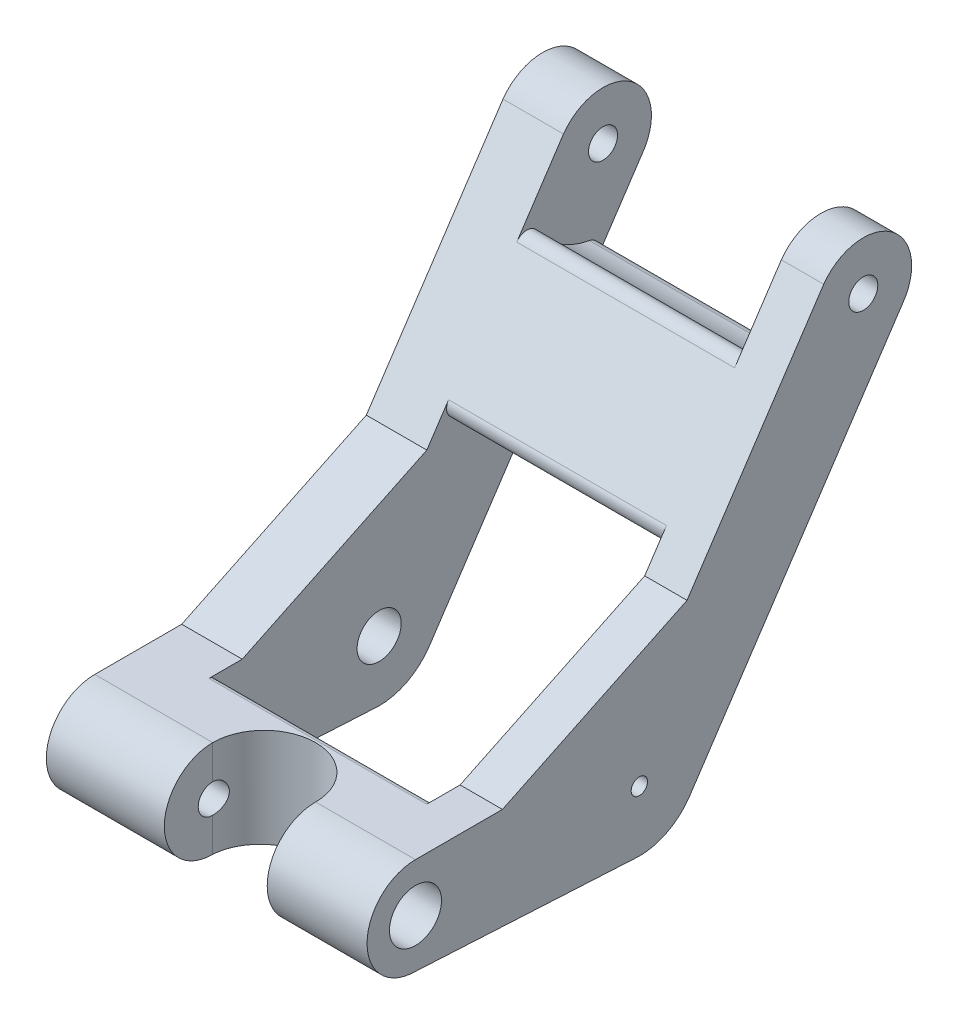
SolidWorks part; units mm, degrees
ref_plane "Front Plane" through (0, 0, 0) normal (0, 0, 1) x (1, 0, 0)
ref_plane "Top Plane" through (0, 0, 0) normal (0, 1, 0) x (1, 0, 0)
ref_plane "Right Plane" through (0, 0, 0) normal (1, 0, 0) x (0, 0, -1)
sketch "Sketch19" plane through (0, 0, 0) normal (1, 0, 0) x (0, 0, -1)
  line L0 (-37, 0) -> (0, 0) construction
  line L5 (0, 0) -> (37, 52) construction
  line L8 (-37, -8) -> (0, -10)
  line L9 (8.1479, -5.7976) -> (43.5183, 47.362)
  line L10 (30.4632, 56.6119) -> (7.8793, 22.6698)
  line L11 (7.8793, 22.6698) -> (-22.6274, 8)
  line L12 (-22.6274, 8) -> (-37, 8)
  arc A0 (8.1479, -5.7976) -> (0, -10) centre (0, 0) cw
  arc A1 (43.5183, 47.362) -> (30.4632, 56.6119) centre (37, 52) ccw
  arc A2 (-37, -8) -> (-37, 8) centre (-37, 0) cw
  circle A3 centre (37, 52) radius 2.4
  circle A4 centre (0, 0) radius 3.65
  circle A5 centre (-37, 0) radius 2.4
  circle A6 centre (0, 0) radius 24 construction
  point P0 (0, 0)
  point P1 (-37, 0)
  point P2 (37, 52)
  dimension "D3" = 37
  dimension "D11" = 7.3
  dimension "D12" = 4.8
  dimension "D13" = 4.8
  dimension "D5" = 8
  dimension "D6" = 10
  dimension "D7" = 8
  dimension "D1" = 37
  dimension "D2" = 52
  dimension "D4" = 0
extrude "Base" add sketch "Sketch19" along normal blind 10
sketch "Sketch20" plane through (10, 0, 0) normal (1, 0, 0) x (0, 0, -1)
  line L0 (30.4632, 56.6119) -> (7.8793, 22.6698) construction
  line L1 (8.1479, -5.7976) -> (43.5183, 47.362) construction
  line L2 (-22.6274, 8) -> (-37, 8) construction
  line L3 (-37, -8) -> (0, -10) construction
  line L7 (22.74, 45.0044) -> (11.4766, 28.0763)
  line L8 (24.3389, 18.5364) -> (36.0548, 36.1447)
  line L9 (-28.1425, 8) -> (-37, 8)
  line L10 (-37, -8) -> (-28.0716, -8.4826)
  circle A0 centre (0, 0) radius 24 construction
  arc A1 (12.2656, 25.1705) -> (21.1622, 18.3347) centre (0, 0) cw
  arc A2 (-27.1721, 6.7586) -> (-27.0515, -7.226) centre (0, 0) ccw
  arc A5 (26.087, 44.9787) -> (34.7383, 39.222) centre (37, 52) ccw
  arc A7 (-27.0515, -7.226) -> (-28.0716, -8.4826) centre (-28.0176, -7.4841) cw
  arc A9 (34.7383, 39.222) -> (36.0548, 36.1447) centre (34.3897, 37.2526) cw
  arc A10 (22.74, 45.0044) -> (26.087, 44.9787) centre (24.4051, 43.8965) cw
  arc A11 (12.2656, 25.1705) -> (11.4766, 28.0763) centre (13.1417, 26.9684) cw
  arc A12 (21.1622, 18.3347) -> (24.3389, 18.5364) centre (22.6738, 19.6443) ccw
  arc A13 (-37, 8) -> (-37, -8) centre (-37, 0) ccw
  arc A14 (-37, 8) -> (-37, -8) centre (-37, 0) ccw construction
  arc A15 (-28.1425, 8) -> (-27.1721, 6.7586) centre (-28.1425, 7) cw
  point P23 (-26.8328, 8)
  point P30 (-26.8328, 8)
  point P33 (-26.6598, -8.5589)
  point P39 (37.9956, 39.0616)
  point P42 (24.6809, 47.9216)
  point P45 (10.1569, 26.0929)
  point P48 (22.8101, 16.2388)
  dimension "D1" = 28
  dimension "D2" = 28
  dimension "D3" = 1
  dimension "D4" = 12.9766
  dimension "D8" = 1
  dimension "D10" = 2
  dimension "D11" = 2
  dimension "D12" = 2
  dimension "D13" = 2
extrude "Connector" add sketch "Sketch20" along normal blind 36
sketch "Sketch21" plane through (46, 0, 0) normal (1, 0, 0) x (0, 0, -1)
  line L1 (-22.6274, 8) -> (-28.1425, 8) construction
  line L2 (-28.1425, 8) -> (-37, 8) construction
  line L3 (-37, -8) -> (-28.0716, -8.4826) construction
  line L4 (-28.0716, -8.4826) -> (0, -10) construction
  line L5 (8.1479, -5.7976) -> (24.3389, 18.5364) construction
  line L6 (24.3389, 18.5364) -> (36.0548, 36.1447) construction
  line L7 (36.0548, 36.1447) -> (43.5183, 47.362) construction
  line L8 (30.4632, 56.6119) -> (22.74, 45.0044) construction
  line L9 (22.74, 45.0044) -> (11.4766, 28.0763) construction
  line L10 (11.4766, 28.0763) -> (7.8793, 22.6698) construction
  line L11 (7.8793, 22.6698) -> (-22.6274, 8) construction
  line L12 (-22.6274, 8) -> (-28.1425, 8)
  line L13 (-28.1425, 8) -> (-37, 8)
  line L14 (-37, -8) -> (-28.0716, -8.4826)
  line L15 (-28.0716, -8.4826) -> (0, -10)
  line L16 (8.1479, -5.7976) -> (24.3389, 18.5364)
  line L17 (24.3389, 18.5364) -> (36.0548, 36.1447)
  line L18 (36.0548, 36.1447) -> (43.5183, 47.362)
  line L19 (30.4632, 56.6119) -> (22.74, 45.0044)
  line L20 (22.74, 45.0044) -> (11.4766, 28.0763)
  line L21 (11.4766, 28.0763) -> (7.8793, 22.6698)
  line L22 (7.8793, 22.6698) -> (-22.6274, 8)
  arc A0 (-37, 8) -> (-37, -8) centre (-37, 0) ccw construction
  arc A1 (0, -10) -> (8.1479, -5.7976) centre (0, 0) ccw construction
  arc A2 (43.5183, 47.362) -> (30.4632, 56.6119) centre (37, 52) ccw construction
  arc A3 (-37, 8) -> (-37, -8) centre (-37, 0) ccw
  arc A4 (0, -10) -> (8.1479, -5.7976) centre (0, 0) ccw
  arc A5 (43.5183, 47.362) -> (30.4632, 56.6119) centre (37, 52) ccw
  circle A6 centre (37, 52) radius 2.4
  circle A7 centre (-37, 0) radius 2.4
  circle A8 centre (0, 0) radius 1.35
  dimension "D1" = 4.8
  dimension "D2" = 4.8
  dimension "D3" = 2.7
extrude "ThinPlate" add sketch "Sketch21" along normal blind 7
sketch "Sketch22" plane through (46, 0, 0) normal (-1, 0, 0) x (0, 0, 1)
  circle A0 centre (0, 0) radius 1.35
  circle A1 centre (0, 0) radius 3
  dimension "D1" = 6
  dimension "D2" = 2.7
extrude "Spacer" add sketch "Sketch22" along normal blind 6
sketch "Sketch23" plane through (0, 8, 0) normal (0, 1, 0) x (1, 0, 0)
  line L0 (10, -27.0176) -> (46, -27.0176) construction
  line L1 (46, -27.0176) -> (46, -45) construction
  line L2 (0, -45) -> (53, -45) construction
  line L3 (46, -45) -> (10, -45) construction
  line L4 (10, -45) -> (10, -27.0176) construction
  line L5 (28, -27.0176) -> (28, -45) construction
  line L6 (53, -37) -> (0, -37) construction
  line L7 (10, -37) -> (46, -37) construction
  line L8 (19.5, -37) -> (19.5, -45.5)
  line L9 (19.5, -28.5) -> (36.5, -28.5) construction
  line L10 (19.5, -28.5) -> (19.5, -45.5) construction
  line L11 (19.5, -45.5) -> (36.5, -45.5) construction
  line L12 (36.5, -28.5) -> (36.5, -45.5) construction
  line L13 (19.5, -45.5) -> (36.5, -45.5)
  line L14 (36.5, -45.5) -> (36.5, -37)
  arc A1 (19.5, -37) -> (36.5, -37) centre (28, -37) cw
  point P12 (46, -37)
  point P13 (28, -37)
  point P14 (10, -37)
  dimension "D1" = 17
  dimension "D2" = 17
  dimension "D3" = 8.5
  dimension "D4" = 8.5
extrude "ShockHole" cut sketch "Sketch23" against normal through all
sketch "Sketch25" plane through (0, 0, 0) normal (-1, 0, 0) x (0, 0, 1)
  circle A0 centre (37, 0) radius 2.4
extrude "ShockScrewHole" cut sketch "Sketch25" against normal through all
sketch "Sketch26" plane through (53, 0, 0) normal (1, 0, 0) x (0, 0, -1)
  circle A0 centre (-37, 0) radius 4.3
  dimension "D1" = 8.6
extrude "BoltMount" cut sketch "Sketch26" against normal blind 8.6
sketch "Sketch27" plane through (0, 0, 0) normal (-1, 0, 0) x (0, 0, 1)
  line L1 (37, -4.3879) -> (40.8, -2.1939)
  line L2 (40.8, -2.1939) -> (40.8, 2.1939)
  line L3 (40.8, 2.1939) -> (37, 4.3879)
  line L4 (37, 4.3879) -> (33.2, 2.1939)
  line L5 (33.2, 2.1939) -> (33.2, -2.1939)
  line L6 (33.2, -2.1939) -> (37, -4.3879)
  circle A0 centre (37, 0) radius 3.8 construction
  dimension "D1" = 7.6
extrude "NutMount" cut sketch "Sketch27" against normal blind 8
